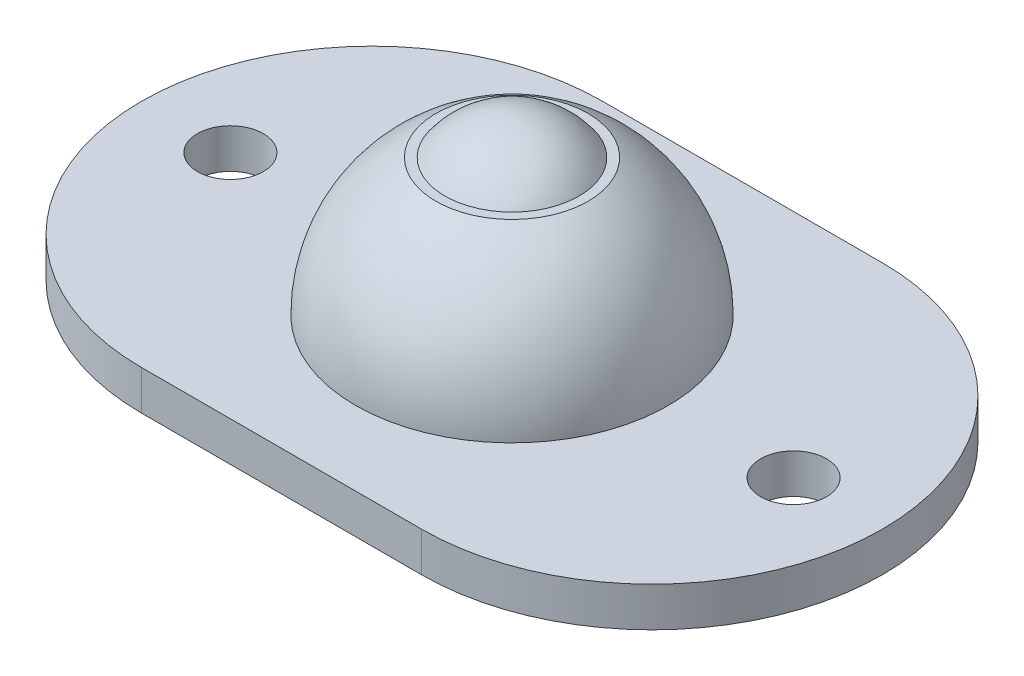
SolidWorks part; units mm, degrees
ref_plane "Front Plane" through (0, 0, 0) normal (0, 0, 1) x (1, 0, 0)
ref_plane "Top Plane" through (0, 0, 0) normal (0, 1, 0) x (1, 0, 0)
ref_plane "Right Plane" through (0, 0, 0) normal (1, 0, 0) x (0, 0, -1)
sketch "Sketch1" plane through (0, 0, 0) normal (0, 1, 0) x (1, 0, 0)
  line L0 (-8.5, 0) -> (8.5, 0) construction
  line L1 (-8.5, 14) -> (8.5, 14)
  line L2 (-8.5, -14) -> (8.5, -14)
  arc A0 (-8.5, 14) -> (-8.5, -14) centre (-8.5, 0) ccw
  arc A1 (8.5, -14) -> (8.5, 14) centre (8.5, 0) ccw
  circle A2 centre (17.1, 0) radius 2
  circle A3 centre (-17.1, 0) radius 2
  point P3 (0, 0)
  point P9 (22.5, 0)
  point P10 (-22.5, 0)
  dimension "D3" = 4
  dimension "D6" = 4
  dimension "D1" = 28
  dimension "D2" = 45
  dimension "D4" = 5.4
  dimension "D5" = 5.4
extrude "Boss-Extrude1" add sketch "Sketch1" along normal blind 2.4
sketch "Sketch2" plane through (0, 0, 0) normal (1, 0, 0) x (0, 0, -1)
  line L0 (14, 2.4) -> (-14, 2.4) construction
  line L1 (-4.6217, 10.7) -> (0, 10.7)
  line L2 (-14, 0) -> (14, 0) construction
  line L3 (0, 2.4) -> (-9.5, 2.4)
  line L4 (-9.5, 2.4) -> (-14, 2.4) construction
  line L5 (14, 2.4) -> (9.5, 2.4) construction
  line L6 (0, 2.4) -> (0, 10.7)
  line L7 (0, 10.7) -> (4.6217, 10.7) construction
  line L8 (9.5, 2.4) -> (0, 2.4) construction
  line L9 (14, 2.4) -> (14, 0) construction
  arc A0 (9.5, 2.4) -> (4.6217, 10.7) centre (0, 2.4) ccw construction
  arc A1 (-9.5, 2.4) -> (9.5, 2.4) centre (0, 2.4) ccw construction
  arc A2 (-4.6217, 10.7) -> (-9.5, 2.4) centre (0, 2.4) ccw
  arc A3 (4.6217, 10.7) -> (-4.6217, 10.7) centre (0, 2.4) ccw construction
  point P1 (0, 0)
  point P14 (0, 0)
  point P15 (0, 0)
  dimension "D1" = 19
  dimension "D2" = 10.7
revolve "Revolve1" add sketch "Sketch2" angle 360 about L6
sketch "Sketch3" plane through (0, 0, 0) normal (1, 0, 0) x (0, 0, -1)
  line L0 (-2.5, 12.8) -> (2.5, 12.8) construction
  line L1 (0, 12.8) -> (0, 2.8)
  line L2 (14, 2.4) -> (-14, 2.4) construction
  arc A0 (0, 12.8) -> (0, 2.8) centre (0, 7.8) ccw
  arc A1 (0, 2.8) -> (0, 12.8) centre (0, 7.8) ccw construction
  point P1 (0, 0)
  point P5 (0, 12.8)
  point P10 (0, 0)
  dimension "D3" = 10
  dimension "D1" = 5
  dimension "D2" = 12.8
revolve "Revolve2" add sketch "Sketch3" angle 360 about L1
